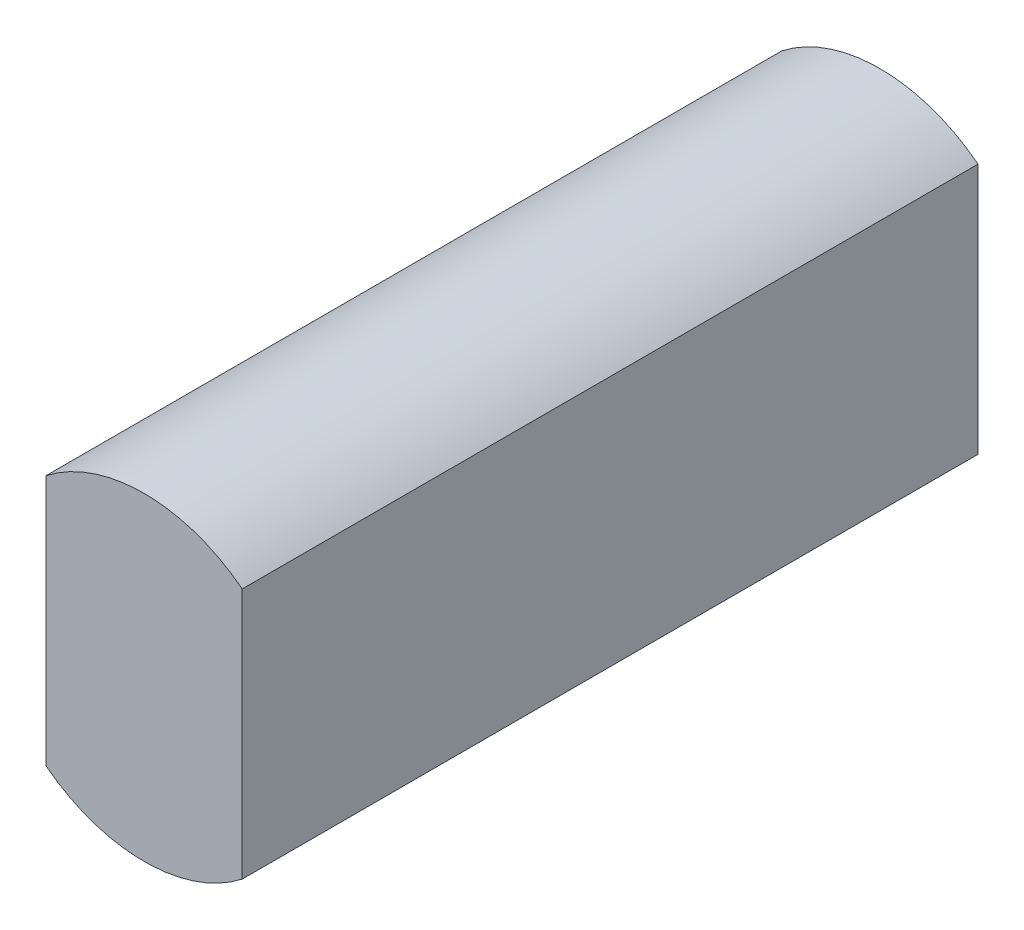
SolidWorks part; units mm, degrees
ref_plane "Front Plane" through (0, 0, 0) normal (0, 0, 1) x (1, 0, 0)
ref_plane "Top Plane" through (0, 0, 0) normal (0, 1, 0) x (1, 0, 0)
ref_plane "Right Plane" through (0, 0, 0) normal (1, 0, 0) x (0, 0, -1)
sketch "Sketch1" plane through (0, 0, 0) normal (0, 0, 1) x (1, 0, 0)
  line L0 (8, 10.247) -> (8, -10.247)
  line L1 (-8, 10.247) -> (-8, -10.247)
  line L2 (-8, 10.247) -> (8, 10.247) construction
  arc A0 (-8, -10.247) -> (8, -10.247) centre (0, 0) ccw
  arc A3 (8, 10.247) -> (-8, 10.247) centre (0, 0) ccw
  dimension "D2" = 26
  dimension "D1" = 16
extrude "Boss-Extrude1" add sketch "Sketch1" against normal blind 40 and the other way blind 20
